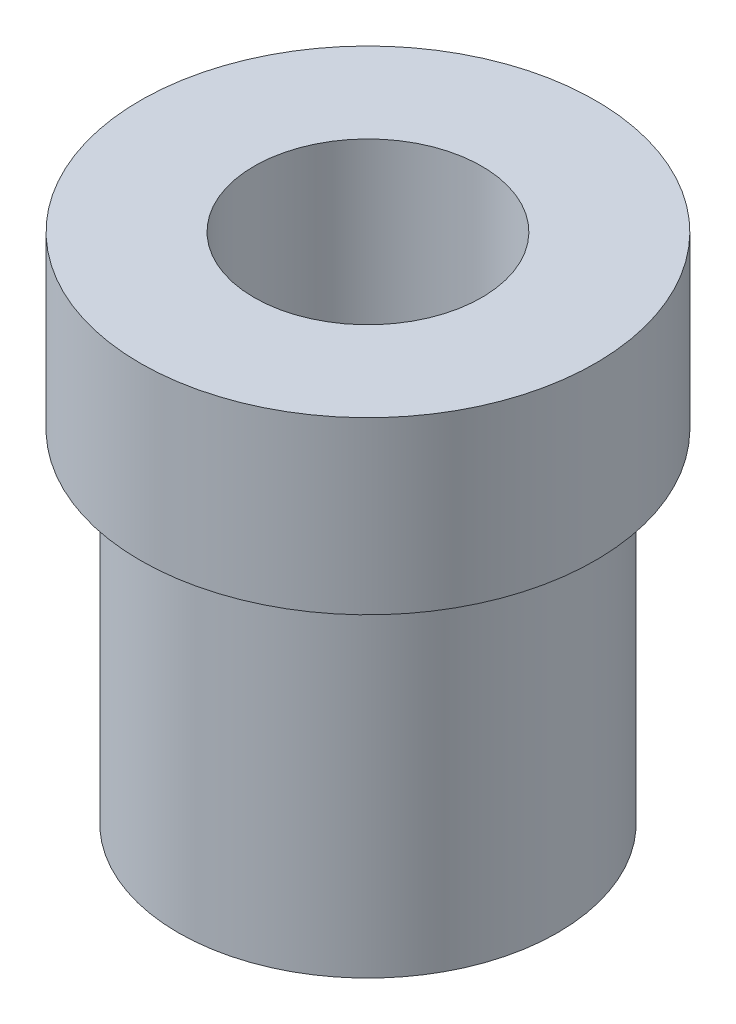
SolidWorks part; units mm, degrees
material "AISI 1035 Steel (SS)"
ref_plane "Front Plane" through (0, 0, 0) normal (0, 0, 1) x (1, 0, 0)
ref_plane "Top Plane" through (0, 0, 0) normal (0, 1, 0) x (1, 0, 0)
ref_plane "Right Plane" through (0, 0, 0) normal (1, 0, 0) x (0, 0, -1)
sketch "Sketch1" plane through (0, 0, 0) normal (0, 0, 1) x (1, 0, 0)
  line L0 (0, 12.4297) -> (0, -14.4099) construction
  line L1 (3, 0) -> (3, -13.5)
  line L2 (3, -13.5) -> (5, -13.5)
  line L3 (5, -13.5) -> (5, -4.5)
  line L4 (5, -4.5) -> (6, -4.5)
  line L5 (6, -4.5) -> (6, 0)
  line L6 (6, 0) -> (3, 0)
  dimension "D1" = 3
  dimension "D2" = 5
  dimension "D3" = 6
  dimension "D4" = 4.5
  dimension "D5" = 13.5
revolve "Revolve1" add sketch "Sketch1" angle 360 about L0
